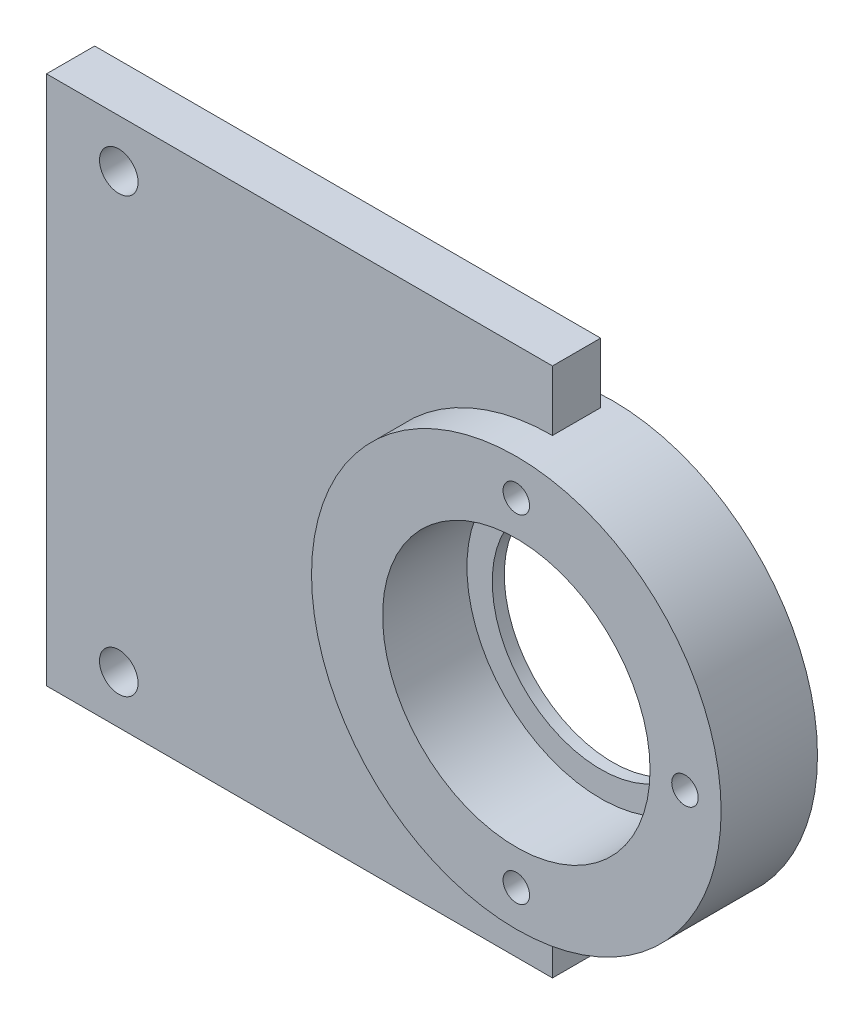
SolidWorks part; units mm, degrees
ref_plane "Front Plane" through (0, 0, 0) normal (0, 0, 1) x (1, 0, 0)
ref_plane "Top Plane" through (0, 0, 0) normal (0, 1, 0) x (1, 0, 0)
ref_plane "Right Plane" through (0, 0, 0) normal (1, 0, 0) x (0, 0, -1)
sketch "Bearing_housing_profile" plane through (0, 0, 0) normal (0, 0, 1) x (1, 0, 0)
  circle A0 centre (0, 0) radius 17
  circle A1 centre (0, 0) radius 11.1
  dimension "D1" = 34
  dimension "D2" = 22.2
extrude "Bearing_housing" add sketch "Bearing_housing_profile" along normal blind 7
sketch "Mounting_web_profile" plane through (0, 0, 0) normal (0, 0, 1) x (1, 0, 0)
  line L1 (-42, -22) -> (0, -22)
  line L2 (-42, -22) -> (-42, 22)
  line L3 (-42, 22) -> (0, 22)
  line L4 (0, -22) -> (0, 22)
  dimension "D1" = 42
  dimension "D2" = 44
  dimension "D3" = 22
extrude "Mounting_web" add sketch "Mounting_web_profile" along normal blind 4
sketch "Bearing_seat_profile" plane through (0, 0, 0) normal (0, 0, 1) x (1, 0, 0)
  circle A0 centre (0, 0) radius 11.1
  dimension "D1" = 22.2
extrude "Bearing_seat" cut sketch "Bearing_seat_profile" along normal through all from offset 50
sketch "Inner_outer_race_retaining_lip_profile" plane through (0, 0, 0) normal (0, 0, 1) x (1, 0, 0)
  circle A0 centre (0, 0) radius 17
  circle A1 centre (0, 0) radius 9
  dimension "D1" = 34
  dimension "D2" = 18
extrude "Inner_outer_race_retaining_lip" add sketch "Inner_outer_race_retaining_lip_profile" along normal blind 1 from offset 1
sketch "Standoff_fasteners_profile" plane through (0, 0, 0) normal (0, 0, 1) x (1, 0, 0)
  circle A0 centre (-36, -18) radius 1.6
  circle A1 centre (-36, 18) radius 1.6
  dimension "D1" = 3.2
  dimension "D2" = 3.2
  dimension "D3" = 36
  dimension "D4" = 18
  dimension "D5" = 18
extrude "Standoff_fasteners" cut sketch "Standoff_fasteners_profile" along normal through all from offset 50
sketch "Bearing_keeper_fasteners_profile" plane through (0, 0, 0) normal (0, 0, 1) x (1, 0, 0)
  circle A0 centre (14, 0) radius 1.1
  circle A1 centre (0, -14) radius 1.1
  circle A2 centre (0, 14) radius 1.1
  dimension "D1" = 2.2
  dimension "D2" = 2.2
  dimension "D3" = 2.2
  dimension "D4" = 14
  dimension "D5" = 14
  dimension "D6" = 14
extrude "Bearing_keeper_fasteners" cut sketch "Bearing_keeper_fasteners_profile" along normal through all from offset 50
